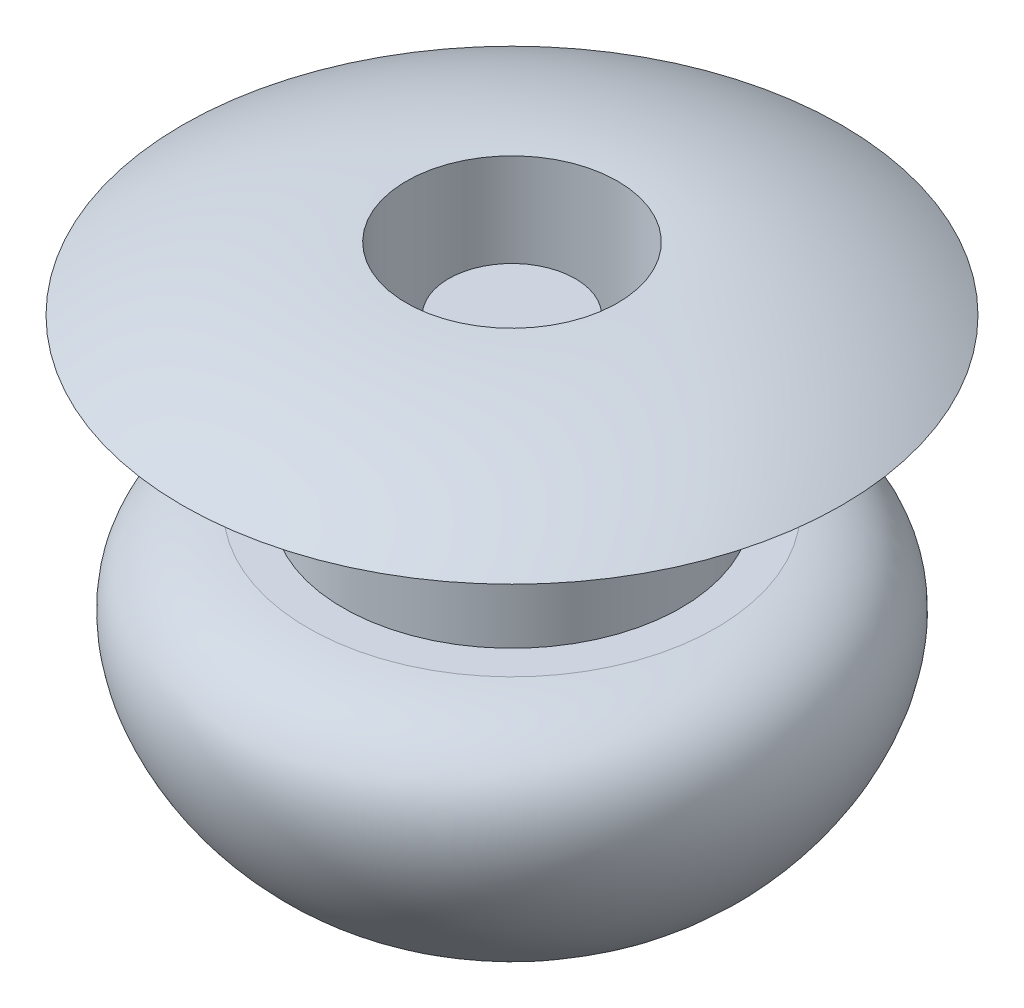
SolidWorks part; units mm, degrees
material "AISI 316 Stal nierdzewna odprężona (SS)"
ref_plane "Płaszczyzna przednia" through (0, 0, 0) normal (0, 0, 1) x (1, 0, 0)
ref_plane "Płaszczyzna górna" through (0, 0, 0) normal (0, 1, 0) x (1, 0, 0)
ref_plane "Płaszczyzna prawa" through (0, 0, 0) normal (1, 0, 0) x (0, 0, -1)
sketch "Szkic1" plane through (0, 0, 0) normal (1, 0, 0) x (0, 0, -1)
  line L1 (0, 0) -> (-0.75, 0)
  line L2 (-0.75, 0) -> (-0.75, -2.2007)
  line L3 (-0.75, -2.2007) -> (-1.25, -2.2007)
  line L4 (-1.25, -2.2007) -> (-1.25, 0.75)
  line L5 (-3.9, 0) -> (-2, 0)
  line L6 (-2, 0) -> (-2, -2)
  line L7 (-2, -2) -> (-2.4139, -2)
  line L8 (0, 0) -> (0, 0.75) construction
  line L9 (0, -2.2007) -> (0, 0)
  line L10 (0, -2.2007) -> (0, -3.7007)
  line L14 (-2, -2) -> (2, -2) construction
  arc A0 (-1.25, 0.75) -> (-3.9, 0) centre (-1.25, -4.3067) ccw
  ellipse E0 centre (0, -2.9507) end of major axis (-1.75, -2.9507) minor radius 0.75 (-0.956, -3.5789) -> (0, -3.7007) ccw
  spline S0 degree 3 poles (-2.4139, -2) (-3.8675, -2.1697) (-3.5289, -4.302) (-1.084, -5.8735) (-0.2718, -3.8749) (-0.956, -3.5789) knots 0 0 0 0 0.464993 0.721928 1 1 1 1
  point P14 (0, 0)
  point P15 (0, 0)
  dimension "D1" = 7.8
  dimension "D2" = 2.5
  dimension "D3" = 4
  dimension "D4" = 0.75
  dimension "D5" = 1.5
  dimension "D6" = 1.5
  dimension "D7" = 3.5
  dimension "D8" = 3.1855
  dimension "D9" = 2.5026
  dimension "D10" = 1.9
  dimension "D11" = 1.5789
  dimension "D12" = 0.5792
  dimension "D13" = 4.8278
  dimension "D14" = 3.3858
  dimension "D15" = 2.8395
  dimension "D16" = 1.25
  dimension "D17" = 0.6409
  dimension "D18" = 0.956
revolve "Obrót1" add sketch "Szkic1" angle 360 about L8
